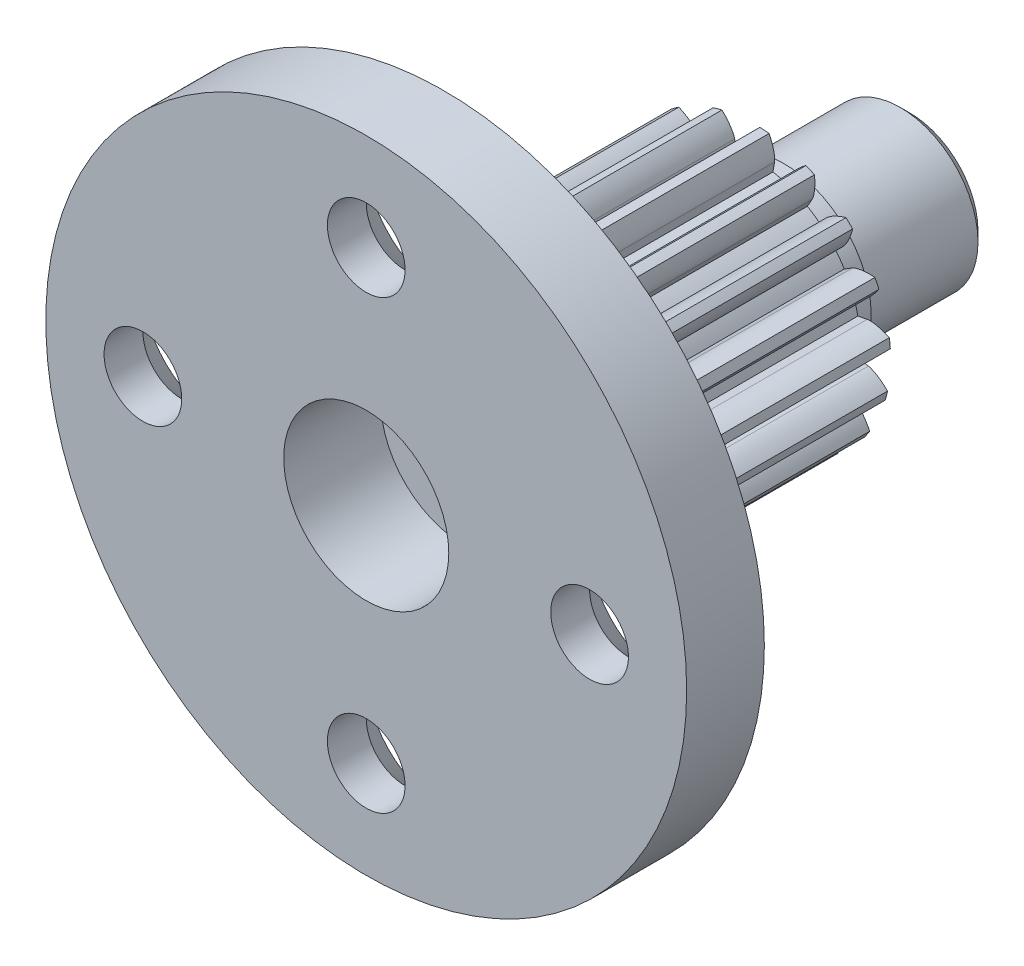
SolidWorks part; units mm, degrees
material "ABS"
ref_plane "Front Plane" through (0, 0, 0) normal (0, 0, 1) x (1, 0, 0)
ref_plane "Top Plane" through (0, 0, 0) normal (0, 1, 0) x (1, 0, 0)
ref_plane "Right Plane" through (0, 0, 0) normal (1, 0, 0) x (0, 0, -1)
sketch "Sketch1" plane through (0, 0, 0) normal (0, 0, 1) x (1, 0, 0)
  circle A0 centre (0, 0) radius 7
  dimension "D1" = 14
extrude "Boss-Extrude1" add sketch "Sketch1" along normal mid plane 16
sketch "Sketch2" plane through (0, 0, 0) normal (0, 0, 1) x (1, 0, 0)
  line L0 (0, 0) -> (5.9201, 0) construction
  line L1 (0, 0) -> (6.2835, -0.4555) construction
  line L2 (0, 0) -> (5.8582, -0.8538) construction
  line L3 (5.9201, 0) -> (5.425, 0)
  line L4 (5.8582, -0.8538) -> (5.3683, -0.7824)
  circle A0 centre (0, 0) radius 6.3 construction
  circle A1 centre (0, 0) radius 5.9201 construction
  circle A2 centre (0, 0) radius 5.425
  circle A3 centre (0, 0) radius 7 construction
  circle A4 centre (0, 0) radius 7
  spline S0 degree 4 poles (5.9201, 0) (5.9221, 0) (5.9278, 0.0002) (5.9453, 0.0013) (5.9797, 0.0051) (6.0221, 0.0122) (6.0706, 0.0226) (6.1172, 0.0343) (6.1569, 0.0455) (6.1963, 0.0576) (6.2354, 0.0705) (6.2825, 0.0873) (6.3388, 0.1089) (6.404, 0.1362) (6.4774, 0.1698) (6.5515, 0.2066) (6.6238, 0.2451) (6.6961, 0.2864) (6.7655, 0.3281) (6.8368, 0.374) (6.9021, 0.4176) (6.9744, 0.4692) (7.0324, 0.5116) (7.1078, 0.5705) (7.1519, 0.6061) (7.2032, 0.6488) (7.2258, 0.6683) (7.2397, 0.6802) knots 0 0 0 0 0 0.005377 0.015084 0.04661 0.092111 0.119476 0.146842 0.174209 0.201575 0.228941 0.256307 0.307035 0.361767 0.4165 0.471232 0.525964 0.580697 0.635429 0.690161 0.744894 0.799626 0.854358 0.909091 0.954545 1 1 1 1 1 construction
  spline S1 degree 4 poles (5.9201, 0) (5.9221, 0) (5.9278, 0.0002) (5.9453, 0.0013) (5.9797, 0.0051) (6.0221, 0.0122) (6.0706, 0.0226) (6.1172, 0.0343) (6.1569, 0.0455) (6.1963, 0.0576) (6.2354, 0.0705) (6.2825, 0.0873) (6.3388, 0.1089) (6.404, 0.1362) (6.4774, 0.1698) (6.5515, 0.2066) (6.6238, 0.2451) (6.6961, 0.2864) (6.7655, 0.3281) (6.8368, 0.374) (6.9021, 0.4176) (6.9744, 0.4692) (7.0324, 0.5116) (7.0914, 0.5577) (7.12, 0.5805) (7.1346, 0.5923) knots 0 0 0 0 0 0.005377 0.015084 0.04661 0.092111 0.119476 0.146842 0.174209 0.201575 0.228941 0.256307 0.307035 0.361767 0.4165 0.471232 0.525964 0.580697 0.635429 0.690161 0.744894 0.799626 0.854358 0.909091 0.909091 0.909091 0.909091 0.909091
  spline S2 degree 4 poles (5.8582, -0.8538) (5.8602, -0.8541) (5.8658, -0.8551) (5.8829, -0.8587) (5.9165, -0.8675) (5.9574, -0.8806) (6.0039, -0.8978) (6.0483, -0.9162) (6.086, -0.9329) (6.1232, -0.9506) (6.16, -0.9691) (6.2043, -0.9925) (6.2568, -1.0219) (6.3174, -1.0584) (6.3852, -1.1022) (6.4532, -1.1493) (6.5192, -1.1978) (6.5848, -1.2491) (6.6475, -1.3004) (6.7114, -1.3561) (6.7698, -1.4086) (6.8338, -1.4701) (6.8851, -1.5205) (6.9512, -1.5896) (6.9898, -1.6312) (7.0344, -1.6808) (7.0539, -1.7034) (7.0659, -1.7172) knots 0 0 0 0 0 0.005377 0.015084 0.04661 0.092111 0.119476 0.146842 0.174209 0.201575 0.228941 0.256307 0.307035 0.361767 0.4165 0.471232 0.525964 0.580697 0.635429 0.690161 0.744894 0.799626 0.854358 0.909091 0.954545 1 1 1 1 1 construction
  spline S3 degree 4 poles (5.8582, -0.8538) (5.8602, -0.8541) (5.8658, -0.8551) (5.8829, -0.8587) (5.9165, -0.8675) (5.9574, -0.8806) (6.0039, -0.8978) (6.0483, -0.9162) (6.086, -0.9329) (6.1232, -0.9506) (6.16, -0.9691) (6.2043, -0.9925) (6.2568, -1.0219) (6.3174, -1.0584) (6.3852, -1.1022) (6.4532, -1.1493) (6.5192, -1.1978) (6.5848, -1.2491) (6.6475, -1.3004) (6.7114, -1.3561) (6.7698, -1.4086) (6.8338, -1.4701) (6.8851, -1.5205) (6.9368, -1.5746) (6.9619, -1.6013) (6.9746, -1.615) knots 0 0 0 0 0 0.005377 0.015084 0.04661 0.092111 0.119476 0.146842 0.174209 0.201575 0.228941 0.256307 0.307035 0.361767 0.4165 0.471232 0.525964 0.580697 0.635429 0.690161 0.744894 0.799626 0.854358 0.909091 0.909091 0.909091 0.909091 0.909091
  dimension "D1" = 12.6
  dimension "D2" = 11.8401
  dimension "D3" = 10.85
  dimension "D4" = 4.146
  dimension "D5" = 4.146
extrude "Cut-Extrude1" cut sketch "Sketch2" against normal through all both and the other way through all contours A2 S3 A4 S1
pattern_circular "CirPattern2" count 18 over 360 about axis through (0, 0, -8) along (0, 0, 1) of "Cut-Extrude1"
sketch "Sketch3" plane through (0, 0, 0) normal (0, 1, 0) x (1, 0, 0)
  line L0 (0, 8) -> (0, 20.841) construction
  line L1 (0, 20.841) -> (0, -26.4333) construction
  line L2 (0, 16) -> (-4, 16)
  line L3 (-4, 16) -> (-4, 9.5)
  line L4 (-4, 9.5) -> (-4.5, 9.5)
  line L6 (-4.5, 9.5) -> (-4.5, 8)
  line L9 (0, 8) -> (-4.5, 8)
  line L10 (1.028, -8) -> (0.942, -8) construction
  line L11 (0, -8) -> (-16.5, -8)
  line L12 (-16.5, -8) -> (-16.5, -12)
  line L13 (-16.5, -12) -> (0, -12)
  line L14 (0, 16) -> (0, -12)
  line L15 (1.6817, 8) -> (1.028, 8) construction
  point P7 (0, -8)
  point P14 (0, 8)
  dimension "D1" = 4
  dimension "D2" = 6.5
  dimension "D3" = 1.5
  dimension "D4" = 0.5
  dimension "D5" = 4
  dimension "D6" = 16.5
revolve "Revolve1" add sketch "Sketch3" angle 360 about L0
chamfer "Chamfer1" distance 0.5 angle 45 1 edges at (4.5, 0, -8)
chamfer "Chamfer2" distance 0.5 angle 45 1 edges at (4, 0, -16)
sketch "Sketch4" plane through (0, 0, 12) normal (0, 0, 1) x (1, 0, 0)
  circle A0 centre (0, 0) radius 2.5
  dimension "D1" = 5
extrude "Cut-Extrude2" cut sketch "Sketch4" against normal through all
sketch "Sketch5" plane through (0, 0, 12) normal (0, 0, 1) x (1, 0, 0)
  circle A0 centre (0, 0) radius 4.25
  dimension "D1" = 8.5
extrude "Cut-Extrude3" cut sketch "Sketch5" against normal blind 5
sketch "Sketch6" plane through (0, 0, 8) normal (0, 0, -1) x (-1, 0, 0)
  circle A0 centre (0, 0) radius 11.5 construction
  circle A1 centre (0, 11.5) radius 2
  circle A2 centre (11.5, 0) radius 2
  circle A3 centre (0, -11.5) radius 2
  circle A4 centre (-11.5, 0) radius 2
  point P14 (0, 0)
  dimension "D1" = 23
  dimension "D2" = 4
  dimension "D3" = 4
extrude "Cut-Extrude4" cut sketch "Sketch6" against normal through all
sketch "Sketch7" plane through (0, 0, 0) normal (0, 1, 0) x (1, 0, 0)
  line L0 (9.5, -12) -> (13.5, -12) construction
  line L1 (13.5, -8) -> (9.5, -8) construction
  line L2 (9.5, -12) -> (13.5, -12)
  line L4 (11.5, -8) -> (11.5, -12) construction
  line L5 (11.5, -8) -> (15.5, -8)
  line L6 (15.5, -8) -> (13.5, -10)
  line L7 (13.5, -10) -> (11.5, -10)
  line L8 (11.5, -8) -> (11.5, -10)
  dimension "D2" = 4
  dimension "D3" = 2
  dimension "D1" = 2
revolve "Cut-Revolve1" cut sketch "Sketch7" angle 360 about L4
pattern_circular "CirPattern3" count 4 over 360 about axis through (0, 0, 0) along (0, 0, 1) of "Cut-Revolve1"
sketch "Sketch8" plane through (0, 0, 8) normal (0, 0, -1) x (-1, 0, 0)
  line L0 (0, 11.5) -> (0, 0) construction
  circle A0 centre (0, 11.5) radius 4
  circle A1 centre (0, 0) radius 11.5 construction
  circle A2 centre (11.5, 0) radius 4
  circle A3 centre (0, -11.5) radius 4
  circle A4 centre (-11.5, 0) radius 4
  point P14 (0, 0)
  dimension "D1" = 23
  dimension "D2" = 8
extrude "Cut-Extrude5" [suppressed] cut sketch "Sketch8" along normal blind 6.5
equation "\"Ns\"= 18"
equation "\"module\"= 0.7"
equation "\"pressure angle\"= 20.0deg"
equation "\"h_a\"= 0.7"
equation "\"h_b\"= 0.875"
equation "\"clr_tip_root\"= 0.17500000000000004"
equation "\"dp_s\"= 12.6"
equation "\"db_s\"= 11.840127021902445"
equation "\"D1@Sketch1\"=\"dp_s\" + 2*\"h_a\""
equation "\"fw_s_calc\"= 6.9645987548691926"
equation "\"D1@Boss-Extrude1\"=\"fw_s_used\""
equation "\"D1@Sketch2\"=\"dp_s\""
equation "\"D2@Sketch2\"= \"db_s\""
equation "\"D3@Sketch2\"=\"dp_s\"- 2*\"h_b\""
equation "\"alpha_s\"= 0.8539582918412556"
equation "\"D4@Sketch2\"= 360 / ( 4 * \"Ns\" ) - \"alpha_s\""
equation "\"beta_s\"= 8.292083416317489"
equation "\"D5@Sketch2\"= 360 / ( 4 * \"Ns\" ) - \"alpha_s\""
equation "\"D1@CirPattern2\"=\"Ns\""
equation "\"Np\"= 45"
equation "\"dp_p\"= 31.499999999999996"
equation "\"db_p\"= 29.600317554756113"
equation "\"fw_p\"= 8.0"
equation "\"alpha_p\"= 0.8539582918412343"
equation "\"beta_p\"= 2.2920834163175314"
equation "\"Nr\"= 108"
equation "\"pressure_angle\"= 20.0deg"
equation "\"h_f\"= 0.875"
equation "\"dp_r\"= 75.6"
equation "\"db_r\"= 71.04076213141467"
equation "\"fw_r\"= 8.0"
equation "\"alpha_r\"= 0.8539582918412449"
equation "\"beta_r\"= 3.374583250349157"
equation "\"bearing_ID\"= 55"
equation "\"bearing_OD\"= 72"
equation "\"bearing_height\"= 9"
equation "\"clearance_planet\"= 1.5"
equation "\"case_dist\"= 6.5"
equation "\"Motor_case_OD_max\"= 111.3"
equation "\"case_mounting_PCD\"= 103.8"
equation "\"bearing mount thickness\"= 8"
equation "\"case_mounting_hole_dia\"= 3"
equation "\"output_mounting_PCD\"= 80"
equation "\"output_mounting_hole_dia\"= 4"
equation "\"clearance_case_mount_holes_shell_thickness\"= 1"
equation "\"motor_case_OD_base\"= 101.8"
equation "\"sec_carrier_thickness\"= 5"
equation "\"sun_coupler_hub_thickness\"= 4"
equation "\"clearance_sun_coupler_sec_carrier\"= 1.5"
equation "\"clearance_motor_and_case\"= 5"
equation "\"motor_OD\"= 86.8"
equation "\"Motor_case_thickness\"= 2.5"
equation "\"Motor_case_ID\"= 96.8"
equation "\"case_mounting_hole_shift\"= 1.0"
equation "\"output_mounting_nut_wrench_size\"= 7"
equation "\"output_mounting_nut_thickness\"= 3.2"
equation "\"case_mounting_hole_allen_socket_dia\"= 5.5"
equation "\"output_mounting_nut_depth\"= 3"
equation "\"case_mounting_bolt_depth\"= 4.5"
equation "\"ring_radial_thickness\"= 5.0"
equation "\"ring_OD\"= 85.6"
equation "\"ring_to_chamfer_clearance\"= 2"
equation "\"Motor_case_OD_base_to_chamfer\"= 5"
equation "\"pattern_offset_from_motor_case_OD_base\"= 3"
equation "\"pattern_bulge_dia\"= 3"
equation "\"pattern_num_bulge\"= 18"
equation "\"pattern_depth\"= 2"
equation "\"motor_height\"= 26.5"
equation "\"case_mounting_wrench_size\"= 5.5"
equation "\"case_mounting_nut_clearance\"= 2"
equation "\"base_plate_thickness\"= 4"
equation "\"case_mounting_nut_thickness\"= 2.4"
equation "\"case_mounting_surface_height\"= 4"
equation "\"motor_mount_hole_PCD\"= 32"
equation "\"motor_mount_hole_dia\"= 4"
equation "\"motor_mount_hole_num\"= 4"
equation "\"central_hole_offset_from_motor_mount_PCD\"= 5"
equation "\"wire_slot_dist_from_center\"= 30"
equation "\"wire_slot_length\"= 10"
equation "\"wire_slot_radius\"= 4"
equation "\"driver_upper_holes_dist_from_center\"= 23"
equation "\"driver_lower_holes_dist_from_center\"= 15"
equation "\"driver_side_holes_dist_from_center\"= 20"
equation "\"driver_mount_holes_dia\"= 2.5"
equation "\"driver_mount_inserts_OD\"= 3.5"
equation "\"driver_mount_thickness\"= 1.5"
equation "\"driver_mount_height\"= 4"
equation "\"air_flow_hole_offset\"= 3"
equation "\"num_planet\"= 3"
equation "\"planet_pin_bolt_dia\"= 5"
equation "\"planet_pin_socket_head_dia\"= 8.5"
equation "\"carrier_PCD\"= 44.099999999999994"
equation "\"planet_shaft_dia\"= 8"
equation "\"planet_shaft_step_offset\"= 1"
equation "\"carrier_trapezoidal_support_sun_offset\"= 5"
equation "\"carrier_trapezoidal_support_hole_PCD_offset_bearing_ID\"= 4"
equation "\"carrier_trapezoidal_support_hole_dia\"= 3"
equation "\"carrier_trapezoidal_support_hole_socket_head_dia\"= 5.5"
equation "\"carrier_bearing_step_width\"= 1.5"
equation "\"standard_clearance_1_5mm\"= 1.5"
equation "\"standard_fillet_1_5mm\"= 1.5"
equation "\"sun_shaft_bearing_OD\"= 16"
equation "\"sun_shaft_bearing_width\"= 5"
equation "\"standard_bearing_insertion_chamfer\"= 0.5"
equation "\"carrier_trapezoidal_support_hole_wrench_size\"= 5.5"
equation "\"planet_pin_bolt_wrench_size\"= 8"
equation "\"planet_bearing_OD\"= 12"
equation "\"planet_bearing_width\"= 3.5"
equation "\"planet_bore\"= 10"
equation "\"motor_output_hole_PCD\"= 23"
equation "\"motor_output_hole_dia\"= 4"
equation "\"motor_output_hole_num\"= 4"
equation "\"sun_shaft_bearing_ID\"= 8"
equation "\"D1@Sketch3\"=\"sun_shaft_bearing_ID\"/2"
equation "\"D2@Sketch3\"=\"sun_shaft_bearing_width\" + \"standard_clearance_1_5mm\""
equation "\"D3@Sketch3\"=\"standard_clearance_1_5mm\""
equation "\"D4@Sketch3\"=\"standard_clearance_1_5mm\"/3"
equation "\"D5@Sketch3\"=\"sun_coupler_hub_thickness\""
equation "\"sun_hub_dia\"= 33.0"
equation "\"D6@Sketch3\"=\"sun_hub_dia\"/2"
equation "\"D1@Chamfer2\"=\"standard_bearing_insertion_chamfer\""
equation "\"D1@Chamfer1\"=\"standard_bearing_insertion_chamfer\""
equation "\"sun_central_bolt_dia\"= 5"
equation "\"sun_central_bolt_socket_head_dia\"= 8.5"
equation "\"D1@Sketch4\"=\"sun_central_bolt_dia\""
equation "\"D1@Cut-Extrude3\"=\"sun_central_bolt_dia\""
equation "\"D1@Sketch5\"=\"sun_central_bolt_socket_head_dia\""
equation "\"fw_s_used\"= 16.0"
equation "\"D1@Sketch6\"=\"motor_output_hole_PCD\""
equation "\"D2@Sketch6\"=\"motor_output_hole_dia\""
equation "\"D3@Sketch6\"=\"motor_output_hole_num\""
equation "\"motor_output_hole_CSK_OD\"= 8"
equation "\"motor_output_hole_CSK_head_height\"= 2.0"
equation "\"D2@Sketch7\"=\"motor_output_hole_CSK_OD\"/2"
equation "\"D3@Sketch7\"=\"motor_output_hole_dia\"/2"
equation "\"D1@CirPattern3\"=\"motor_output_hole_num\""
equation "\"D1@Sketch7\"=\"motor_output_hole_CSK_head_height\""
equation "\"D1@Sketch8\"=\"motor_output_hole_PCD\""
equation "\"D2@Sketch8\"=\"motor_output_hole_CSK_OD\""
equation "\"D1@Cut-Extrude5\"=\"sec_carrier_thickness\"+\"standard_clearance_1_5mm\""
equation "\"Cut-Extrude5\"= IIF ( ( \"Ns\" * \"module\" + 2 * \"h_a\" ) < ( \"motor_output_hole_PCD\" - \"motor_output_hole_CSK_OD\" ) , \"suppressed\" , \"unsuppressed\" )"
